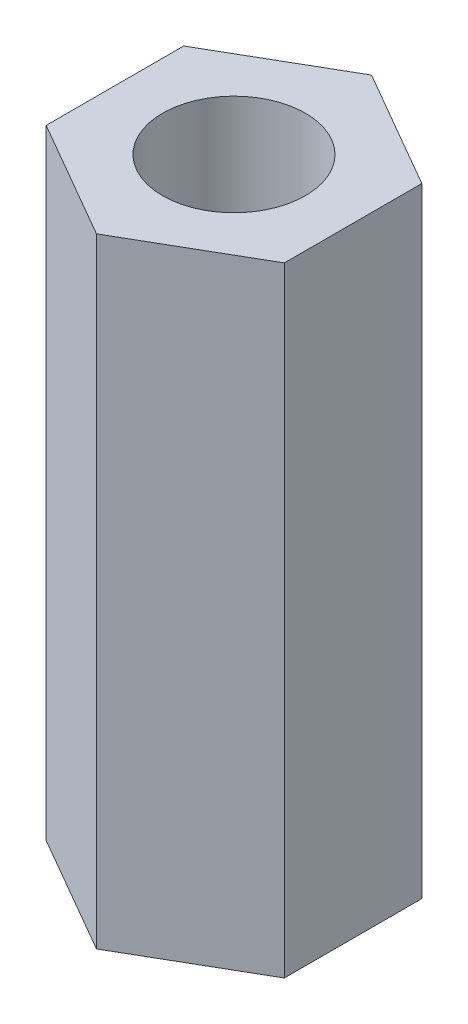
SolidWorks part; units mm, degrees
ref_plane "前基準面" through (0, 0, 0) normal (0, 0, 1) x (1, 0, 0)
ref_plane "上基準面" through (0, 0, 0) normal (0, 1, 0) x (1, 0, 0)
ref_plane "右基準面" through (0, 0, 0) normal (1, 0, 0) x (0, 0, -1)
sketch "草圖1" plane through (0, 0, 0) normal (0, 1, 0) x (1, 0, 0)
  line L1 (0, 2.8868) -> (-2.5, 1.4434)
  line L2 (-2.5, 1.4434) -> (-2.5, -1.4434)
  line L3 (-2.5, -1.4434) -> (0, -2.8868)
  line L4 (0, -2.8868) -> (2.5, -1.4434)
  line L5 (2.5, -1.4434) -> (2.5, 1.4434)
  line L6 (2.5, 1.4434) -> (0, 2.8868)
  circle A0 centre (0, 0) radius 2.5 construction
  dimension "D1" = 5
extrude "填料-伸長1" add sketch "草圖1" along normal blind 13
sketch "草圖2" plane through (0, 13, 0) normal (0, 1, 0) x (-1, 0, 0)
  circle A0 centre (0, 0) radius 1.5
  dimension "D1" = 3
extrude "除料-伸長1" cut sketch "草圖2" against normal up to next
